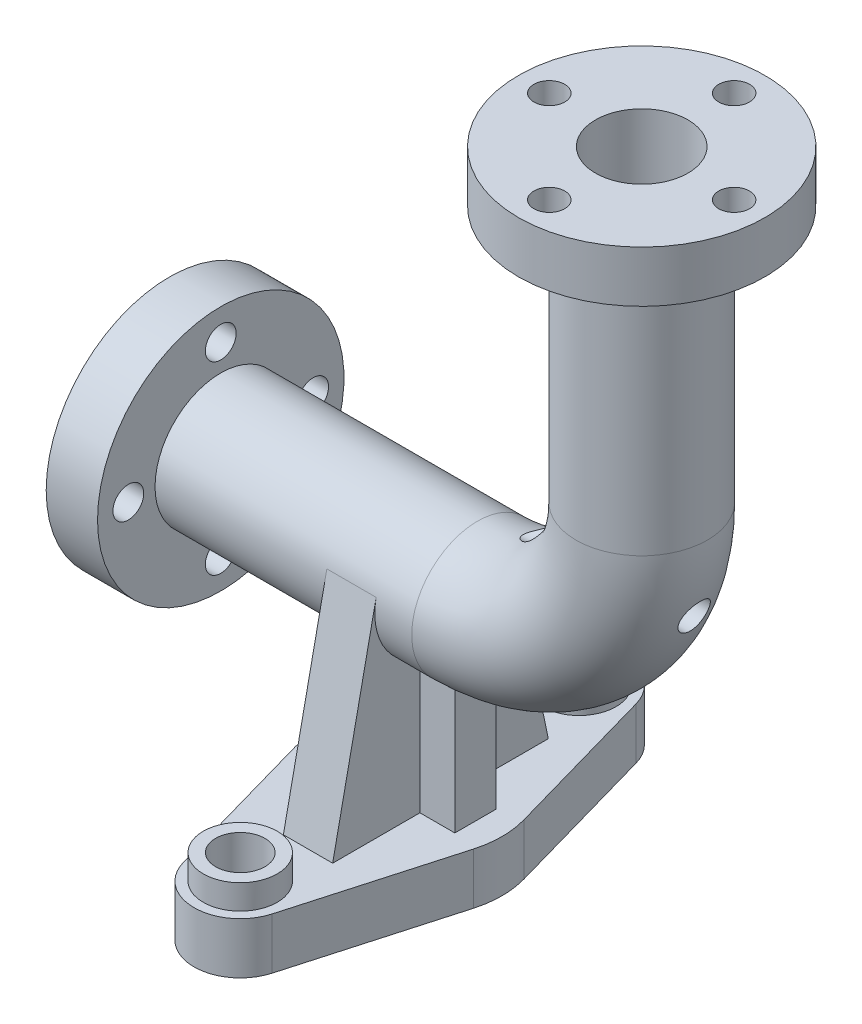
SolidWorks part; units mm, degrees
ref_plane "Front Plane" through (0, 0, 0) normal (0, 0, 1) x (1, 0, 0)
ref_plane "Top Plane" through (0, 0, 0) normal (0, 1, 0) x (1, 0, 0)
ref_plane "Right Plane" through (0, 0, 0) normal (1, 0, 0) x (0, 0, -1)
sketch "Sketch1" plane through (0, 0, 0) normal (0, 0, 1) x (1, 0, 0)
  line L0 (0, 0) -> (150, 0)
  line L1 (230, 80) -> (230, 230)
  arc A0 (150, 0) -> (230, 80) centre (150, 80) ccw
  dimension "D2" = 80
  dimension "D1" = 150
  dimension "D3" = 150
sketch "Sketch2" plane through (0, 0, 0) normal (1, 0, 0) x (0, 0, -1)
  circle A0 centre (0, 0) radius 32
  circle A1 centre (0, 0) radius 22.5
  dimension "D1" = 45
  dimension "D2" = 64
sweep "Sweep1" add profiles "Sketch2" path "Sketch1"
sketch "Sketch3" plane through (0, 230, 0) normal (0, 1, 0) x (1, 0, 0)
  circle A0 centre (230, 0) radius 22.5 construction
  circle A1 centre (230, 0) radius 22.5
  circle A2 centre (230, 0) radius 60
  dimension "D1" = 120
extrude "Boss-Extrude1" add sketch "Sketch3" against normal blind 25
sketch "Sketch4" plane through (0, 0, 0) normal (-1, 0, 0) x (0, 0, 1)
  circle A0 centre (0, 0) radius 22.5 construction
  circle A1 centre (0, 0) radius 22.5
  circle A2 centre (0, 0) radius 60
  dimension "D1" = 120
extrude "Boss-Extrude2" add sketch "Sketch4" against normal blind 25
hole_wizard "Hole1" positions "Sketch5" profile "Sketch6" legacy end condition through all
sketch "Sketch5" plane through (0, 230, 0) normal (0, 1, 0) x (1, 0, 0)
  line L0 (230, 0) -> (275, 0) construction
  point P0 (275, 0)
  dimension "D1" = 45
sketch "Sketch6" plane through (275, 230, 0) normal (1, 0, 0) x (0, 0, 1)
  line L0 (0, 0) -> (0, 290)
  line L1 (0, 290) -> (7.5, 290)
  line L2 (7.5, 290) -> (7.5, 0)
  line L3 (7.5, 0) -> (0, 0)
  line L4 (0, 110) -> (0, -10) construction
  dimension "Diameter" = 15
  dimension "Depth" = 290
pattern_circular "CirPattern1" count 4 over 360 about axis through (230, 0, 0) along (0, 1, 0) of "Hole1"
hole_wizard "Hole2" positions "Sketch7" profile "Sketch8" legacy end condition through all
sketch "Sketch7" plane through (0, 0, 0) normal (-1, 0, 0) x (0, 0, 1)
  point P0 (45, 0)
  point P4 (0, 0)
  dimension "D1" = 45
sketch "Sketch8" plane through (0, 0, 45) normal (0, 1, 0) x (0, 0, 1)
  line L0 (0, 0) -> (0, 290)
  line L1 (0, 290) -> (7.5, 290)
  line L2 (7.5, 290) -> (7.5, 0)
  line L3 (7.5, 0) -> (0, 0)
  line L4 (0, 110) -> (0, -10) construction
  dimension "Diameter" = 15
  dimension "Depth" = 290
pattern_circular "CirPattern2" count 4 over 360 about axis through (0, 0, 0) along (1, 0, 0) of "Hole2"
ref_plane "Plane1" through (0, -120, 0) normal (0, 1, 0) x (1, 0, 0)
sketch "Sketch9" plane through (0, -120, 0) normal (0, 1, 0) x (1, 0, 0)
  line L0 (0, 0) -> (143.9017, 0) construction
  line L1 (0, 60) -> (0, -60) construction
  line L2 (95.3529, 88.6364) -> (73.7059, 12.2727)
  line L3 (138.6471, 88.6364) -> (160.2941, 12.2727)
  line L4 (95.3529, -88.6364) -> (73.7059, -12.2727)
  line L5 (138.6471, -88.6364) -> (160.2941, -12.2727)
  arc A0 (73.7059, 12.2727) -> (73.7059, -12.2727) centre (117, 0) ccw
  arc A1 (95.3529, -88.6364) -> (138.6471, -88.6364) centre (117, -82.5) ccw
  arc A3 (95.3529, 88.6364) -> (138.6471, 88.6364) centre (117, 82.5) cw
  arc A4 (160.2941, -12.2727) -> (160.2941, 12.2727) centre (117, 0) ccw
  dimension "D1" = 90
  dimension "D2" = 45
  dimension "D3" = 117
  dimension "D4" = 82.5
extrude "Boss-Extrude3" add sketch "Sketch9" along normal blind 25 separate body
sketch "Sketch10" plane through (0, -95, 0) normal (0, 1, 0) x (1, 0, 0)
  circle A0 centre (117, -82.5) radius 18
  circle A1 centre (117, 82.5) radius 18
  dimension "D1" = 36
extrude "Boss-Extrude4" add sketch "Sketch10" along normal blind 12
hole_wizard "Hole3" positions "Sketch11" profile "Sketch12" legacy end condition through all
sketch "Sketch11" plane through (0, -83, 0) normal (0, 1, 0) x (1, 0, 0)
  point P0 (117, -82.5)
  point P3 (117, 82.5)
sketch "Sketch12" plane through (117, -83, 82.5) normal (1, 0, 0) x (0, 0, 1)
  line L0 (0, 0) -> (0, 37)
  line L1 (0, 37) -> (12, 37)
  line L2 (12, 37) -> (12, 0)
  line L3 (12, 0) -> (0, 0)
  line L4 (0, 110) -> (0, -10) construction
  dimension "Diameter" = 24
  dimension "Depth" = 37
sketch "Sketch13" plane through (0, 0, 0) normal (0, 0, 1) x (1, 0, 0)
  line L0 (95.3529, -120) -> (138.6471, -120) construction
  line L1 (85, -31) -> (149, -31)
  line L2 (85, -31) -> (85, -120)
  line L3 (85, -120) -> (149, -120)
  line L4 (149, -31) -> (149, -120)
  line L5 (117, -120) -> (117, -10.1319) construction
  point P8 (117, -120)
  dimension "D1" = 31
  dimension "D2" = 64
extrude "Boss-Extrude5" add sketch "Sketch13" along normal mid plane 20
ref_plane "Plane2" through (120, 0, 0) normal (1, 0, 0) x (0, 0, -1)
sketch "Sketch14" plane through (120, 0, 0) normal (1, 0, 0) x (0, 0, -1)
  line L0 (-31.3261, 6.5328) -> (-52.5, -95)
  line L2 (-88.6364, -95) -> (-12.2727, -95) construction
  line L3 (0, -95) -> (0, 85.0944) construction
  line L4 (12.2727, -95) -> (-12.2727, -95) construction
  line L5 (31.3261, 6.5328) -> (52.5, -95)
  line L6 (-52.5, -95) -> (52.5, -95)
  circle A0 centre (0, 0) radius 32 construction
  arc A1 (-31.3261, 6.5328) -> (31.3261, 6.5328) centre (0, 0) ccw
  point P5 (30.6041, 9.995)
  point P6 (28.8174, 18.5624)
  point P14 (-25.7751, 33.1505)
  dimension "D1" = 105
extrude "Boss-Extrude6" add sketch "Sketch14" along normal mid plane 24
